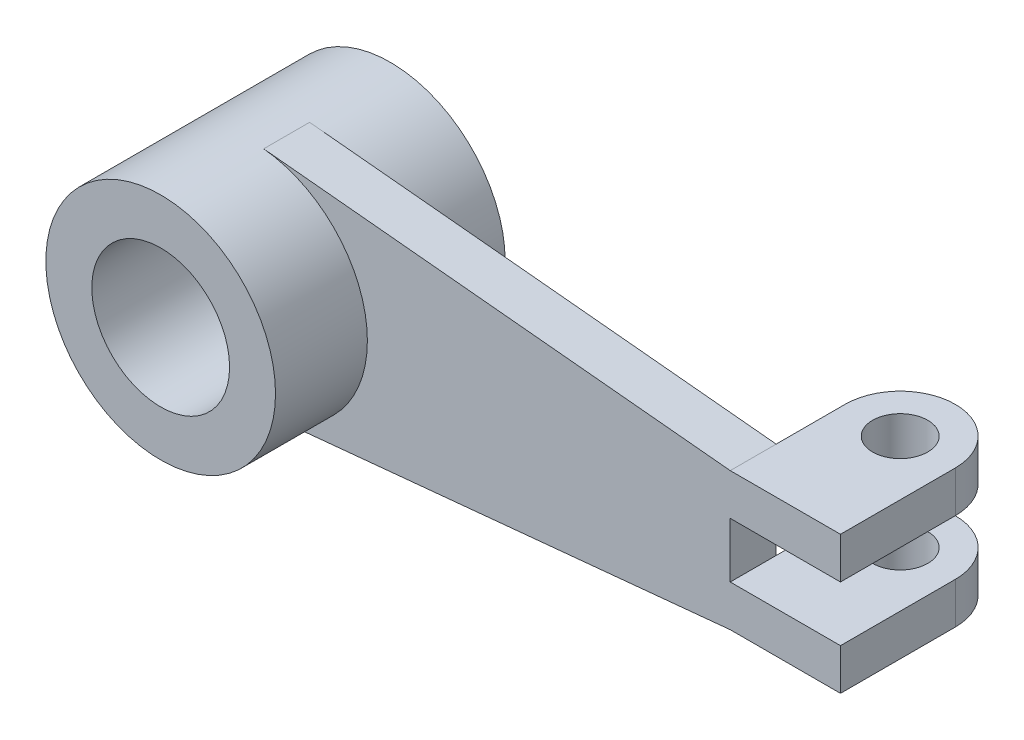
SolidWorks part; units mm, degrees
ref_plane "Front Plane" through (0, 0, 0) normal (0, 0, 1) x (1, 0, 0)
ref_plane "Top Plane" through (0, 0, 0) normal (0, 1, 0) x (1, 0, 0)
ref_plane "Right Plane" through (0, 0, 0) normal (1, 0, 0) x (0, 0, -1)
sketch "Sketch1" plane through (0, 0, 0) normal (0, 0, 1) x (1, 0, 0)
  circle A0 centre (0, 0) radius 25
  circle A1 centre (0, 0) radius 15
  dimension "D1" = 50
  dimension "D2" = 30
extrude "Boss-Extrude1" add sketch "Sketch1" along normal mid plane 50
sketch "Sketch3" plane through (0, 0, -25) normal (0, 0, -1) x (-1, 0, 0)
  line L0 (-104, 15) -> (-104, -15)
  line L1 (0, 0) -> (-112.5534, 0) construction
  line L2 (-104, 15) -> (-2.4208, 24.8825)
  line L3 (-104, -15) -> (-2.4208, -24.8825)
  circle A0 centre (0, 0) radius 25 construction
  arc A1 (-2.4208, 24.8825) -> (-2.4208, -24.8825) centre (0, 0) ccw
  point P5 (-104, 0)
  dimension "D1" = 104
  dimension "D2" = 30
extrude "Boss-Extrude2" add sketch "Sketch3" along normal blind 10 from offset 30 offset against normal yes
sketch "Sketch6" plane through (0, 0, 0) normal (0, 1, 0) x (1, 0, 0)
  line L5 (104, -5) -> (104, 20)
  line L6 (104, 5) -> (104, -5) construction
  line L7 (104, -5) -> (128, -5)
  line L8 (128, -5) -> (128, 20)
  line L9 (2.4208, -5) -> (104, -5) construction
  arc A2 (128, 20) -> (104, 20) centre (116, 20) ccw
  dimension "D1" = 24
  dimension "D2" = 25
extrude "Boss-Extrude3" add sketch "Sketch6" against normal blind 9 from offset 15
mirror "Mirror1" about plane through (0, 0, 0) normal (0, 1, 0) of "Boss-Extrude3"
hole_wizard "Hole1" positions "Sketch7" profile "Sketch8" legacy end condition through all
sketch "Sketch7" plane through (0, 15, 0) normal (0, 1, 0) x (1, 0, 0)
  point P0 (116, 20)
sketch "Sketch8" plane through (116, 15, -20) normal (1, 0, 0) x (0, 0, 1)
  line L0 (0, 0) -> (0, 40)
  line L1 (0, 40) -> (6, 40)
  line L2 (6, 40) -> (6, 0)
  line L3 (6, 0) -> (0, 0)
  line L4 (0, 110) -> (0, -10) construction
  dimension "Diameter" = 12
  dimension "Depth" = 40
